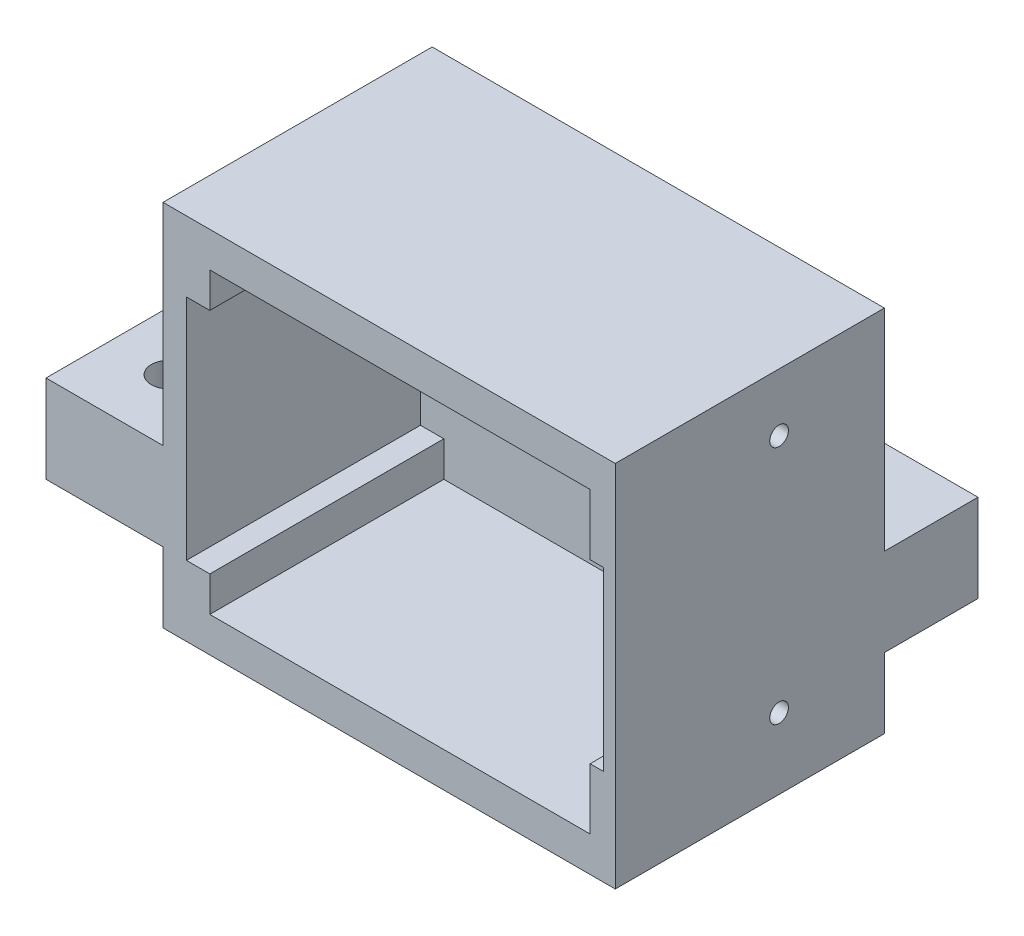
SolidWorks part; units mm, degrees
ref_plane "Front Plane" through (0, 0, 0) normal (0, 0, 1) x (1, 0, 0)
ref_plane "Top Plane" through (0, 0, 0) normal (0, 1, 0) x (1, 0, 0)
ref_plane "Right Plane" through (0, 0, 0) normal (1, 0, 0) x (0, 0, -1)
sketch "Sketch1" plane through (0, 0, 0) normal (0, 1, 0) x (1, 0, 0)
  line L1 (0, 0) -> (38.65, 0)
  line L2 (0, 0) -> (0, 23)
  line L3 (0, 23) -> (38.65, 23)
  line L4 (38.65, 0) -> (38.65, 23)
  dimension "D1" = 38.65
  dimension "D2" = 23
extrude "Boss-Extrude1" add sketch "Sketch1" along normal blind 31.5
sketch "Sketch3" plane through (0, 0, 0) normal (0, 0, 1) x (1, 0, 0)
  line L0 (2, 25.5) -> (2, 6)
  line L1 (2, 6) -> (4, 6)
  line L2 (4, 6) -> (4, 3)
  line L3 (4, 3) -> (36.5, 3)
  line L4 (36.5, 3) -> (36.5, 8.2)
  line L5 (36.5, 8.2) -> (37.65, 8.2)
  line L6 (37.65, 8.2) -> (37.65, 23.3)
  line L7 (37.65, 23.3) -> (36.5, 23.3)
  line L8 (36.5, 23.3) -> (36.5, 28.5)
  line L9 (36.5, 28.5) -> (4, 28.5)
  line L10 (4, 28.5) -> (4, 25.5)
  line L11 (4, 25.5) -> (2, 25.5)
  line L16 (0, 0) -> (38.65, 0)
  line L17 (38.65, 0) -> (38.65, 31.5)
  line L18 (38.65, 31.5) -> (0, 31.5)
  line L19 (0, 31.5) -> (0, 0)
  line L20 (0, 0) -> (38.65, 0)
  line L21 (38.65, 0) -> (38.65, 31.5)
  line L22 (38.65, 31.5) -> (0, 31.5)
  line L23 (0, 31.5) -> (0, 0)
  dimension "D2" = 3
  dimension "D3" = 19.5
  dimension "D4" = 3
  dimension "D5" = 2
  dimension "D6" = 2
  dimension "D7" = 3
  dimension "D8" = 32.5
  dimension "D9" = 1.15
  dimension "D10" = 15.1
  dimension "D11" = 5.2
  dimension "D12" = 31.5
  dimension "D1" = 0
extrude "Cut-Extrude1" cut sketch "Sketch3" against normal blind 20 contours L11 L0 L1 L2 L3 L4 L5 L6 L7 L8 L9 L10
sketch "Sketch4" plane through (36.5, 0, 0) normal (-1, 0, 0) x (0, 0, 1)
  line L0 (0, 3) -> (0, 8.2) construction
  line L1 (0, 8.2) -> (-20, 8.2) construction
  line L2 (-20, 8.2) -> (-20, 3) construction
  line L3 (-20, 3) -> (0, 3) construction
  line L4 (0, 23.3) -> (0, 28.5)
  line L5 (0, 28.5) -> (-20, 28.5)
  line L6 (-20, 28.5) -> (-20, 23.3)
  line L7 (-20, 23.3) -> (0, 23.3)
  line L8 (0, 23.3) -> (0, 28.5)
  line L9 (0, 28.5) -> (-20, 28.5)
  line L10 (-20, 28.5) -> (-20, 23.3)
  line L11 (-20, 23.3) -> (0, 23.3)
  line L12 (0, 8.2) -> (0, 23.3) construction
  line L13 (0, 23.3) -> (-20, 23.3) construction
  line L14 (-20, 23.3) -> (-20, 8.2) construction
  line L15 (-20, 8.2) -> (0, 8.2) construction
  line L16 (0, 3) -> (0, 8.2)
  line L17 (0, 8.2) -> (-20, 8.2)
  line L18 (-20, 8.2) -> (-20, 3)
  line L19 (-20, 3) -> (0, 3)
  line L20 (0, 8.2) -> (0, 23.3)
  line L21 (0, 23.3) -> (-20, 23.3)
  line L22 (-20, 23.3) -> (-20, 8.2)
  line L23 (-20, 8.2) -> (0, 8.2)
  circle A0 centre (-14, 26.55) radius 0.8
  circle A1 centre (-14, 6.05) radius 0.8
  dimension "D5" = 1.6
  dimension "D2" = 20.5
  dimension "D3" = 3.25
  dimension "D4" = 6
  dimension "D1" = 0
extrude "Cut-Extrude2" cut sketch "Sketch4" against normal up to surface (2.15 mm away) contours A0 | A1 up to face at (38.65, 15.75, -11.5)
sketch "Sketch5" plane through (4, 0, 0) normal (1, 0, 0) x (0, 0, -1)
  line L4 (0, 25.5) -> (0, 6)
  line L5 (0, 6) -> (20, 6)
  line L6 (20, 6) -> (20, 25.5)
  line L7 (20, 25.5) -> (0, 25.5)
  line L8 (0, 25.5) -> (0, 6)
  line L9 (0, 6) -> (20, 6)
  line L10 (20, 6) -> (20, 25.5)
  line L11 (20, 25.5) -> (0, 25.5)
  circle A0 centre (17.6, 26.5) radius 0.8
  circle A1 centre (17.6, 6) radius 0.8
  dimension "D3" = 1.6
  dimension "D2" = 20.5
  dimension "D4" = 1
  dimension "D5" = 2.4
  dimension "D1" = 0
extrude "Cut-Extrude3" [suppressed] cut sketch "Sketch5" against normal up to surface (4 mm away) contours A0 | A1
sketch "Sketch7" plane through (0, 0, 0) normal (0, -1, 0) x (1, 0, 0)
  line L0 (38.65, 0) -> (38.65, -23) construction
  line L1 (0, -23) -> (38.65, -23)
  line L2 (0, -23) -> (0, -31)
  line L3 (0, -31) -> (38.65, -31)
  line L4 (38.65, -23) -> (38.65, -31)
  line L5 (0, -27) -> (38.65, -27) construction
  line L6 (1, -23) -> (1, -31)
  line L7 (-5, 0) -> (-5, -23) construction
  line L8 (0, 0) -> (-10, 0)
  line L9 (0, 0) -> (0, -23)
  line L10 (0, -23) -> (-10, -23)
  line L11 (-10, 0) -> (-10, -23)
  circle A0 centre (9, -27) radius 1.5
  circle A1 centre (30.65, -27) radius 1.5
  circle A2 centre (-5, -5.5) radius 1.5
  circle A3 centre (-5, -17.5) radius 1.5
  line M7 (0, 0) -> (0, -23)
  dimension "D3" = 3
  dimension "D7" = 3
  dimension "D1" = 8
  dimension "D2" = 1
  dimension "D4" = 8
  dimension "D5" = 8
  dimension "D6" = 10
  dimension "D8" = 5.5
  dimension "D9" = 5.5
extrude "Boss-Extrude2" add sketch "Sketch7" against normal blind 7.5 from offset 6 contours L5 L6 L3 L4 A1 A0 | L8 L11 L10 A3 A2 M7
